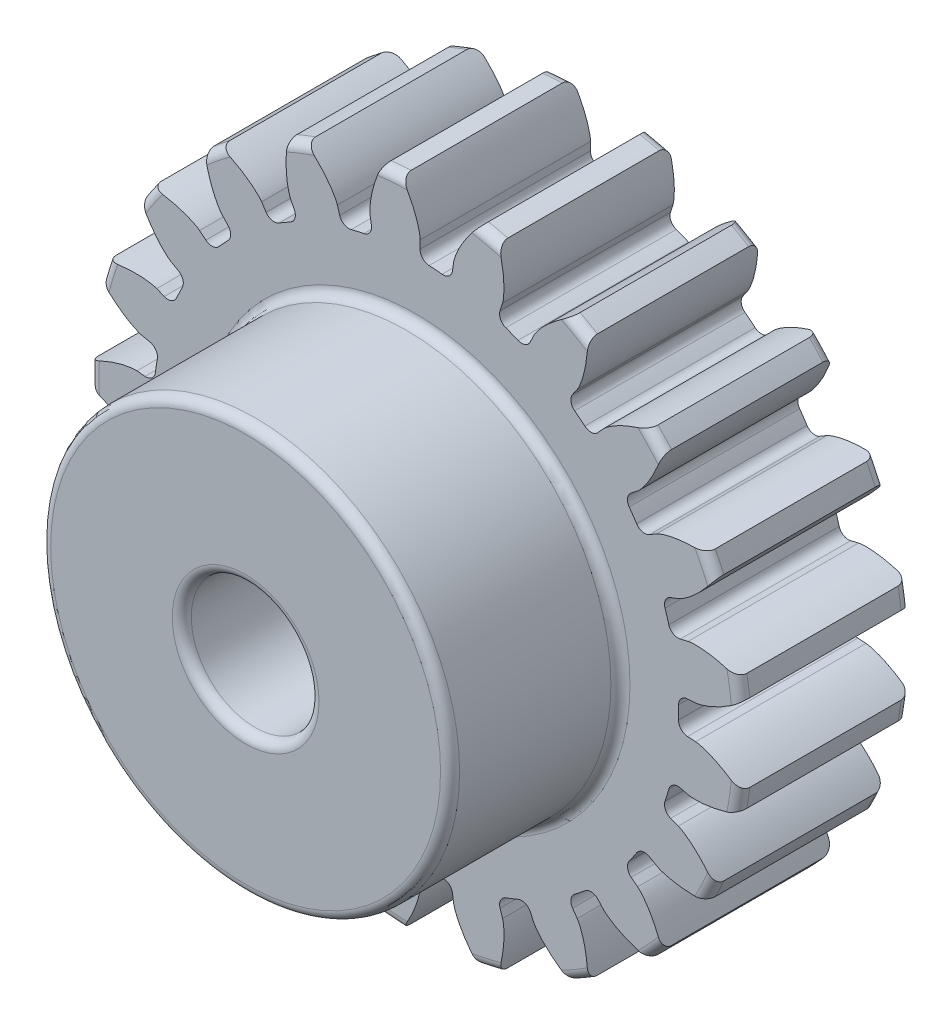
SolidWorks part; units mm, degrees
ref_plane "Front Plane" through (0, 0, 0) normal (0, 0, 1) x (1, 0, 0)
ref_plane "Top Plane" through (0, 0, 0) normal (0, 1, 0) x (1, 0, 0)
ref_plane "Right Plane" through (0, 0, 0) normal (1, 0, 0) x (0, 0, -1)
sketch "Sketch1" plane through (0, 0, 0) normal (0, 0, 1) x (1, 0, 0)
  line L0 (0, 0) -> (0, 11.1125) construction
  line L1 (-3.5715, 12.4124) -> (3.5715, 9.8126) construction
  circle A0 centre (0, 0) radius 9.7896 construction
  circle A1 centre (0, 0) radius 12.1708 construction
  circle A2 centre (0, 0) radius 11.1125 construction
  circle A3 centre (0, 0) radius 10.4423 construction
  circle A4 centre (0, 0) radius 2.3813 construction
  circle A5 centre (0, 0) radius 7.62 construction
  point P8 (304.8, 0)
  point P13 (266.7, 0)
  dimension "OD | Outside Diameter" = 24.3417
  dimension "Root Diameter" = 19.5792
  dimension "Gear Pitch Diameter" = 22.225
  dimension "Base Diameter" = 20.8847
  dimension "For Shaft Diameter" = 4.7625
  dimension "Hub Diameter" = 15.24
  dimension "Pressure Angle" = 20
  dimension "Number of Teeth" = 533.4
  dimension "Gear Pitch | Diametral Pitch" = 609.6
sketch "Sketch2" plane through (0, 0, 0) normal (1, 0, 0) x (0, 0, -1)
  line L0 (-6.35, 0) -> (6.35, 0) construction
  line L1 (-6.35, 12.1708) -> (6.35, 12.1708) construction
  point P2 (0, 12.1708)
  point P4 (0, 0)
  point P6 (0, 12.1708)
  dimension "Overall Width" = 12.7
  dimension "Hub Width" = 6.35
  dimension "Face Width" = 6.35
sketch "Sketch3" plane through (0, 0, 0) normal (0, 0, 1) x (1, 0, 0)
  circle A0 centre (0, 0) radius 12.1708
  circle A1 centre (0, 0) radius 12.1708 construction
extrude "Boss-Extrude1" add sketch "Sketch3" against normal up to vertex (6.35 mm away) and the other way up to vertex (6.35 mm away) up to point (0, 0, -6.35) other way up to point (0, 0, 6.35)
sketch "Sketch5" plane through (0, 0, 0) normal (1, 0, 0) x (0, 0, -1)
  line L1 (-6.35, 12.1708) -> (0, 12.1708)
  line L2 (-6.35, 12.1708) -> (-6.35, 7.62)
  line L3 (-6.35, 7.62) -> (0, 7.62)
  line L4 (0, 12.1708) -> (0, 7.62)
  line L11 (6.35, 2.3813) -> (-6.35, 2.3812)
  line L12 (6.35, 2.3813) -> (6.35, 0)
  line L13 (6.35, 0) -> (-6.35, 0)
  line L14 (-6.35, 2.3812) -> (-6.35, 0)
  point P5 (0, 2.3813)
  point P12 (0, 7.62)
revolve "Cut-Revolve1" cut sketch "Sketch5" angle 360 about L0
fillet "Fillet2" radius 0.3551 6 edges at (12.1708, 0, -6.35) (2.3813, 0, -6.35) (2.3812, 0, 6.35) (7.62, 0, 0) (12.1708, 0, 0) (7.62, 0, 6.35)
sketch "Sketch4" plane through (0, 0, 0) normal (0, 0, 1) x (1, 0, 0)
  line L0 (0, 0) -> (9.772, 0.586) construction
  line L2 (0, 0) -> (9.772, -0.586) construction
  line L4 (9.772, 0.586) -> (10.4236, 0.6251)
  line L5 (10.4236, -0.6251) -> (9.772, -0.586)
  arc A0 (9.772, 0.586) -> (9.772, -0.586) centre (0, 0) cw
  arc A3 (12.0846, 1.4466) -> (12.0846, -1.4466) centre (0, 0) cw
  circle A4 centre (0, 0) radius 12.1708 construction
  spline S0 degree 4 poles (10.4236, 0.6251) (10.4264, 0.6253) (10.4341, 0.6259) (10.4487, 0.6276) (10.4724, 0.631) (10.5026, 0.6362) (10.5415, 0.6439) (10.5871, 0.6544) (10.6371, 0.6672) (10.6913, 0.6826) (10.7451, 0.6993) (10.7985, 0.7171) (10.8516, 0.736) (10.9156, 0.7602) (10.992, 0.7909) (11.0807, 0.8294) (11.1807, 0.8762) (11.2817, 0.927) (11.3805, 0.9797) (11.4795, 1.036) (11.5747, 1.0926) (11.6727, 1.1545) (11.7627, 1.2132) (11.8624, 1.2823) (11.9426, 1.3391) (12.0473, 1.4176) (12.1087, 1.465) (12.1802, 1.5217) (12.2117, 1.5475) (12.2311, 1.5634) knots 0 0 0 0 0 0.005377 0.015084 0.028532 0.04661 0.064855 0.092111 0.119476 0.146842 0.174209 0.201575 0.228941 0.256307 0.307035 0.361767 0.4165 0.471232 0.525964 0.580697 0.635429 0.690161 0.744894 0.799626 0.854358 0.909091 0.954545 1 1 1 1 1 construction
  spline S1 degree 4 poles (10.4236, 0.6251) (10.4264, 0.6253) (10.4341, 0.6259) (10.4487, 0.6276) (10.4724, 0.631) (10.5026, 0.6362) (10.5415, 0.6439) (10.5871, 0.6544) (10.6371, 0.6672) (10.6913, 0.6826) (10.7451, 0.6993) (10.7985, 0.7171) (10.8516, 0.736) (10.9156, 0.7602) (10.992, 0.7909) (11.0807, 0.8294) (11.1807, 0.8762) (11.2817, 0.927) (11.3805, 0.9797) (11.4795, 1.036) (11.5747, 1.0926) (11.6727, 1.1545) (11.7627, 1.2132) (11.8624, 1.2823) (11.9426, 1.3391) (12.0246, 1.4005) (12.0643, 1.4309) (12.0846, 1.4466) knots 0 0 0 0 0 0.005377 0.015084 0.028532 0.04661 0.064855 0.092111 0.119476 0.146842 0.174209 0.201575 0.228941 0.256307 0.307035 0.361767 0.4165 0.471232 0.525964 0.580697 0.635429 0.690161 0.744894 0.799626 0.854358 0.909091 0.909091 0.909091 0.909091 0.909091
  spline S2 degree 4 poles (10.4236, -0.6251) (10.4264, -0.6253) (10.4341, -0.6259) (10.4487, -0.6276) (10.4724, -0.631) (10.5026, -0.6362) (10.5415, -0.6439) (10.5871, -0.6544) (10.6371, -0.6672) (10.6913, -0.6826) (10.7451, -0.6993) (10.7985, -0.7171) (10.8516, -0.736) (10.9156, -0.7602) (10.992, -0.7909) (11.0807, -0.8294) (11.1807, -0.8762) (11.2817, -0.927) (11.3805, -0.9797) (11.4795, -1.036) (11.5747, -1.0926) (11.6727, -1.1545) (11.7627, -1.2132) (11.8624, -1.2823) (11.9426, -1.3391) (12.0473, -1.4176) (12.1087, -1.465) (12.1802, -1.5217) (12.2117, -1.5475) (12.2311, -1.5634) knots 0 0 0 0 0 0.005377 0.015084 0.028532 0.04661 0.064855 0.092111 0.119476 0.146842 0.174209 0.201575 0.228941 0.256307 0.307035 0.361767 0.4165 0.471232 0.525964 0.580697 0.635429 0.690161 0.744894 0.799626 0.854358 0.909091 0.954545 1 1 1 1 1 construction
  spline S3 degree 4 poles (10.4236, -0.6251) (10.4264, -0.6253) (10.4341, -0.6259) (10.4487, -0.6276) (10.4724, -0.631) (10.5026, -0.6362) (10.5415, -0.6439) (10.5871, -0.6544) (10.6371, -0.6672) (10.6913, -0.6826) (10.7451, -0.6993) (10.7985, -0.7171) (10.8516, -0.736) (10.9156, -0.7602) (10.992, -0.7909) (11.0807, -0.8294) (11.1807, -0.8762) (11.2817, -0.927) (11.3805, -0.9797) (11.4795, -1.036) (11.5747, -1.0926) (11.6727, -1.1545) (11.7627, -1.2132) (11.8624, -1.2823) (11.9426, -1.3391) (12.0246, -1.4005) (12.0643, -1.4309) (12.0846, -1.4466) knots 0 0 0 0 0 0.005377 0.015084 0.028532 0.04661 0.064855 0.092111 0.119476 0.146842 0.174209 0.201575 0.228941 0.256307 0.307035 0.361767 0.4165 0.471232 0.525964 0.580697 0.635429 0.690161 0.744894 0.799626 0.854358 0.909091 0.909091 0.909091 0.909091 0.909091
  dimension "D1" = 19.5792
extrude "Cut-Extrude1" cut sketch "Sketch4" against normal through all both and the other way through all
fillet "Fillet1" radius 0.3551 2 edges at (9.772, -0.586, -3.175) (9.772, 0.586, -3.175)
pattern_circular "CirPattern1" count 21 over 360 about axis through (0, 0, 6.35) along (0, 0, -1) of "Cut-Extrude1", "Fillet1"
equation "\"Root Diameter@Sketch1\"=\"Root Diameter\""
equation "\"OD | Outside Diameter@Sketch1\"=\"Outside Diameter\""
equation "\"D1@CirPattern1\"=\"Number of Teeth\""
equation "\"Diametral Pitch\"= 24"
equation "\"Number of Teeth\"= 21"
equation "\"Pressure Angle\"=20"
equation "\"Pitch Diameter\"= \"Number of Teeth\" / \"Diametral Pitch\""
equation "\"Base Diameter\"= \"Pitch Diameter\" * cos ( \"Pressure Angle\" )"
equation "\"Outside Diameter\"= ( \"Number of Teeth\" + 2 ) / \"Diametral Pitch\""
equation "\"Dedendum\"= 1.25 / \"Diametral Pitch\""
equation "\"Root Diameter\"= \"Pitch Diameter\" - ( 2 * \"Dedendum\" )"
equation "\"Pitch Angle\"= 360deg / \"Number of Teeth\""
equation "\"Alpha\"= sqr ( \"Pitch Diameter\" ^ 2 - \"Base Diameter\" ^ 2 ) / \"Base Diameter\" * 180 / PI - \"Pressure Angle\""
equation "\"Beta\"= ( \"Pitch Angle\" / 4 - \"Alpha\" )"
equation "\"Phi\"= sqr ( ( \"Outside Diameter\" / 2 ) ^ 2 - ( \"Base Diameter\" / 2 ) ^ 2 ) / ( \"Base Diameter\" / 2 )"
equation "\"Addendum\"= 1 / \"Diametral Pitch\""
equation "\"WorkingDepth\"= 2 / \"Diametral Pitch\""
equation "\"WholeDepth\"= 2.25 / \"Diametral Pitch\""
equation "\"Clearance\"= 0.25 / \"Diametral Pitch\""
equation "\"ToothThickness\"= ( pi * 2 ) / \"Diametral Pitch\""
equation "\"CircularPitch\"= pi / \"Diametral Pitch\""
equation "\"Number of Teeth@Sketch1\"=\"Number of Teeth\""
equation "\"Gear Pitch | Diametral Pitch@Sketch1\"=\"Diametral Pitch\""
equation "\"Pressure Angle@Sketch1\"=\"Pressure Angle\""
equation "\"Gear Pitch Diameter@Sketch1\"=\"Pitch Diameter\""
equation "\"Base Diameter@Sketch1\"=\"Base Diameter\""
equation "\"Fillet\"= \"Clearance\" * cos ( \"Pressure Angle\" ) * tan ( ( 90 + \"Pressure Angle\" ) / 2 )"
equation "\"D1@Fillet1\"=\"Fillet\""
equation "\"D1@Sketch4\"=if( \"Base Diameter\">\"Root Diameter\",\"Root Diameter\",\"Base Diameter\"-.00001)"
equation "\"D1@Fillet2\"=\"Fillet\""
